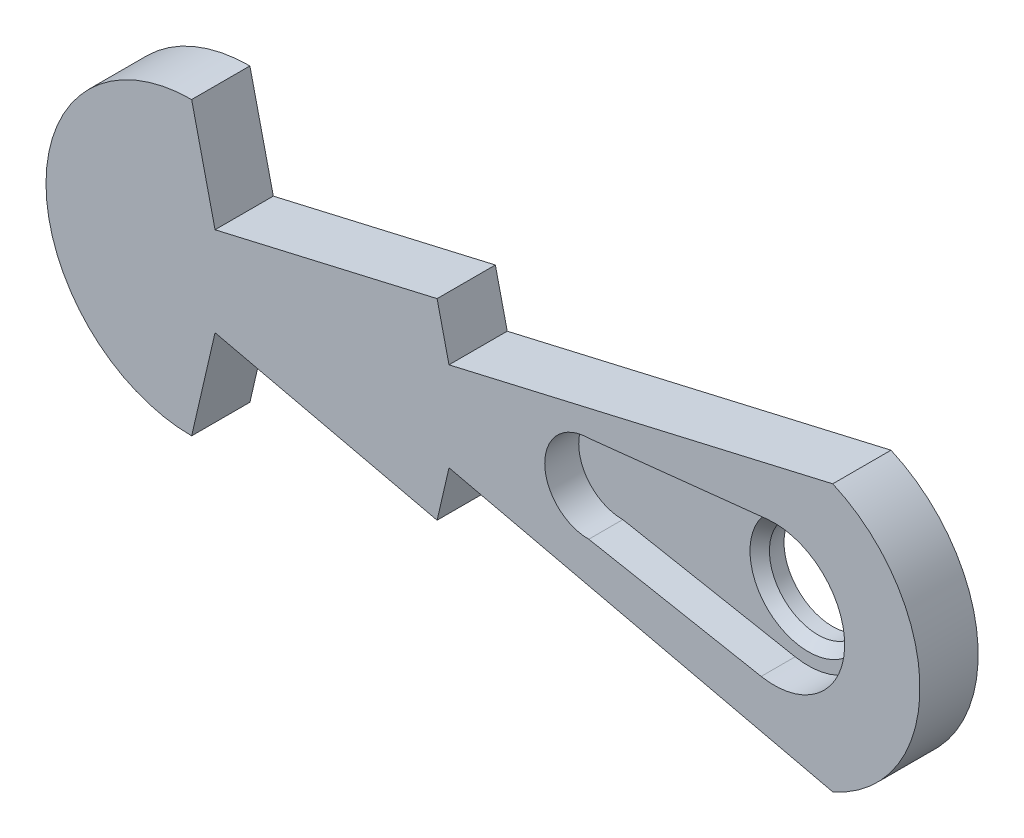
SolidWorks part; units mm, degrees
ref_plane "Ön Düzlem" through (0, 0, 0) normal (0, 0, 1) x (1, 0, 0)
ref_plane "Üst Düzlem" through (0, 0, 0) normal (0, 1, 0) x (1, 0, 0)
ref_plane "Sağ Düzlem" through (0, 0, 0) normal (1, 0, 0) x (0, 0, -1)
sketch "Çizim1" plane through (0, 0, 0) normal (0, 0, 1) x (1, 0, 0)
  line L0 (-35.653, 0) -> (24.347, 0) construction
  line L1 (-35.653, 15) -> (24.347, 15)
  line L2 (-35.653, -15) -> (24.347, -15)
  arc A0 (-35.653, 15) -> (-35.653, -15) centre (-35.653, 0) ccw
  arc A1 (24.347, -15) -> (24.347, 15) centre (24.347, 0) ccw
  point P3 (-5.653, 0)
  dimension "D1" = 15
  dimension "D2" = 60
extrude "Yükseklik-Ekstrüzyon1" add sketch "Çizim1" along normal blind 4
sketch "Çizim2" plane through (0, 0, 4) normal (0, 0, 1) x (1, 0, 0)
  line L0 (-35.653, 15) -> (-33.2438, 4.5907)
  line L1 (-33.2438, 4.5907) -> (11.7295, 15)
  line L2 (24.347, 15) -> (-35.653, 15) construction
  line L3 (11.7295, 15) -> (11.5926, 15.5911)
  line L4 (11.5926, 15.5911) -> (9.0388, 15)
  line L5 (9.0388, 15) -> (9.2838, 13.9414)
  line L6 (9.2838, 13.9414) -> (13.8573, 15)
  line L7 (13.8573, 15) -> (14.1023, 13.9414)
  line L8 (14.1023, 13.9414) -> (18.6759, 15)
  line L9 (18.6759, 15) -> (17.1385, 21.6425)
  line L10 (17.1385, 21.6425) -> (-11.5602, 15)
  line L11 (-11.5602, 15) -> (-9.1509, 4.5907)
  line L12 (-9.1509, 4.5907) -> (35.8223, 15)
  line L13 (-35.653, 0) -> (-9.6355, 0) construction
  line L14 (-9.1509, -4.5907) -> (35.8223, -15)
  line L15 (-35.653, -15) -> (24.347, -15)
  line L16 (24.347, 15) -> (-35.653, 15)
  line L17 (-35.653, -15) -> (24.347, -15)
  line L18 (35.8223, 15) -> (-35.653, 15)
  line L19 (-11.5602, -15) -> (-9.1509, -4.5907)
  line L20 (17.1385, -21.6425) -> (-11.5602, -15)
  line L21 (18.6759, -15) -> (17.1385, -21.6425)
  line L22 (14.1023, -13.9414) -> (18.6759, -15)
  line L23 (13.8573, -15) -> (14.1023, -13.9414)
  line L24 (9.2838, -13.9414) -> (13.8573, -15)
  line L25 (9.0388, -15) -> (9.2838, -13.9414)
  line L26 (11.5926, -15.5911) -> (9.0388, -15)
  line L27 (11.7295, -15) -> (11.5926, -15.5911)
  line L28 (-33.2438, -4.5907) -> (11.7295, -15)
  line L29 (-35.653, -15) -> (-33.2438, -4.5907)
  arc A2 (-35.653, 15) -> (-35.653, -15) centre (-35.653, 0) ccw
  arc A3 (24.347, -15) -> (24.347, 15) centre (24.347, 0) ccw
  arc A5 (24.347, -15) -> (24.347, 15) centre (24.347, 0) ccw
  line M7 (-35.653, -15) -> (24.347, -15)
  line M9 (24.347, 15) -> (-35.653, 15)
  dimension "D1" = 0
extrude "Kes-Ekstrüzyon1" cut sketch "Çizim2" against normal blind 4 contours L0 L1 M9 | L3 L4 M9 | L5 L6 M9 | L7 L8 M9 | L9 L10 M9 | L11 L12 M9 | L19 L17 L14 | L21 L17 L20 | L23 L17 L22 | L25 L17 L24 | L27 L17 L26 | L29 L28 M7
sketch "Çizim3" plane through (0, 0, 4) normal (0, 0, 1) x (1, 0, 0)
  circle A0 centre (24.347, 0) radius 5
  dimension "D1" = 10
extrude "Kes-Ekstrüzyon2" cut sketch "Çizim3" against normal blind 4
sketch "Çizim5" plane through (0, 0, 4) normal (0, 0, 1) x (1, 0, 0)
  line L3 (-10.376, -9.8836) -> (-11.5602, -15)
  line L4 (-11.5602, -15) -> (11.7295, -15)
  line L5 (11.7295, -15) -> (-10.376, -9.8836)
  line L6 (-10.376, -9.8836) -> (-11.5602, -15)
  line L7 (-11.5602, -15) -> (11.7295, -15)
  line L8 (11.7295, -15) -> (-10.376, -9.8836)
  line L9 (-11.5602, 15) -> (-10.376, 9.8836)
  line L10 (-10.376, 9.8836) -> (11.7295, 15)
  line L11 (11.7295, 15) -> (-11.5602, 15)
  line L12 (-11.5602, 15) -> (-10.376, 9.8836)
  line L13 (-10.376, 9.8836) -> (11.7295, 15)
  line L14 (11.7295, 15) -> (-11.5602, 15)
  dimension "D1" = 0
  dimension "D2" = 0
extrude "Kes-Ekstrüzyon3" cut sketch "Çizim5" against normal blind 4
sketch "Çizim10" plane through (0, 0, 4) normal (0, 0, 1) x (1, 0, 0)
  line L0 (23.5737, 7.2086) -> (5.173, 5.2349)
  line L1 (22.9992, -7.1236) -> (5.2458, -3.7648)
  circle A0 centre (24.347, 0) radius 7.25
  arc A1 (5.173, 5.2349) -> (5.2458, -3.7648) centre (5.2094, 0.7351) ccw
  circle M2 centre (24.347, 0) radius 5
  dimension "D1" = 14.5
  dimension "D2" = 9
extrude "Kes-Ekstrüzyon4" cut sketch "Çizim10" against normal blind 3.5 contours L0 A1 L1 A0 | A0 M2
sketch "Çizim11" plane through (0, 0, 0) normal (0, 0, -1) x (-1, 0, 0)
  line L8 (33.2438, -4.5907) -> (35.653, -15)
  line L9 (35.653, 15) -> (33.2438, 4.5907)
  line L10 (33.2438, 4.5907) -> (10.376, 9.8836)
  line L11 (10.376, 9.8836) -> (9.1509, 4.5907)
  line L12 (9.1509, 4.5907) -> (-30.3694, 13.7379)
  line L13 (-30.3694, -13.7379) -> (9.1509, -4.5907)
  line L14 (9.1509, -4.5907) -> (10.376, -9.8836)
  line L15 (10.376, -9.8836) -> (33.2438, -4.5907)
  line L16 (33.2438, -4.5907) -> (35.653, -15)
  line L17 (35.653, 15) -> (33.2438, 4.5907)
  line L18 (33.2438, 4.5907) -> (10.376, 9.8836)
  line L19 (10.376, 9.8836) -> (9.1509, 4.5907)
  line L20 (9.1509, 4.5907) -> (-30.3694, 13.7379)
  line L21 (-30.3694, -13.7379) -> (9.1509, -4.5907)
  line L22 (9.1509, -4.5907) -> (10.376, -9.8836)
  line L23 (10.376, -9.8836) -> (33.2438, -4.5907)
  circle A0 centre (-24.347, 0) radius 5 construction
  circle A1 centre (-24.347, 0) radius 5
  arc A2 (35.653, -15) -> (35.653, 15) centre (35.653, 0) ccw
  arc A3 (-30.3694, 13.7379) -> (-30.3694, -13.7379) centre (-24.347, 0) ccw
  arc A4 (35.653, -15) -> (35.653, 15) centre (35.653, 0) ccw
  arc A5 (-30.3694, 13.7379) -> (-30.3694, -13.7379) centre (-24.347, 0) ccw
  dimension "D1" = 0
extrude "Yükseklik-Ekstrüzyon3" add sketch "Çizim11" along normal blind 2
chamfer "Pah2" distance 1 angle 45 1 edges at (29.347, 0, 0.5)
